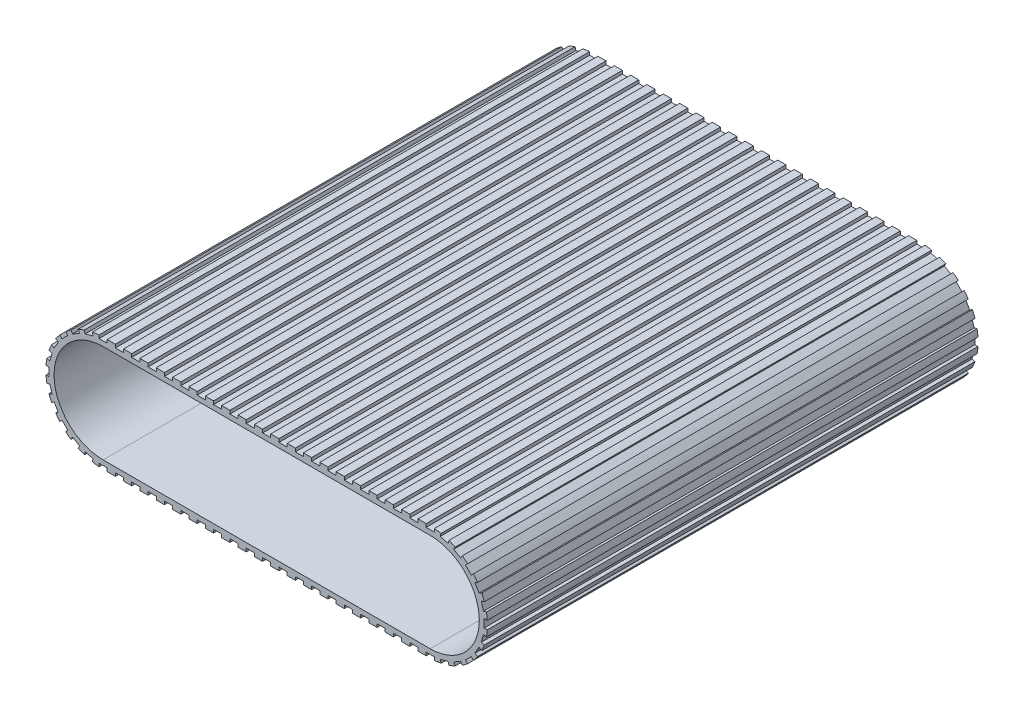
SolidWorks part; units mm, degrees
ref_plane "前视基准面" through (0, 0, 0) normal (0, 0, 1) x (1, 0, 0)
ref_plane "上视基准面" through (0, 0, 0) normal (0, 1, 0) x (1, 0, 0)
ref_plane "右视基准面" through (0, 0, 0) normal (1, 0, 0) x (0, 0, -1)
sketch "草图1" plane through (0, 0, 0) normal (0, 0, 1) x (1, 0, 0)
  line L0 (-100, 0) -> (100, 0) construction
  line L1 (-100, 35) -> (100, 35)
  line L2 (-100, -35) -> (100, -35)
  line L3 (-100, 0) -> (100, 0) construction
  line L4 (-100, 30) -> (100, 30)
  line L5 (-100, -30) -> (100, -30)
  arc A0 (-100, 35) -> (-100, -35) centre (-100, 0) ccw
  arc A1 (100, -35) -> (100, 35) centre (100, 0) ccw
  arc A2 (-100, 30) -> (-100, -30) centre (-100, 0) ccw
  arc A3 (100, -30) -> (100, 30) centre (100, 0) ccw
  point P3 (0, 0)
  point P8 (0, 0)
  dimension "D1" = 35
  dimension "D3" = 30
  dimension "D2" = 200
extrude "凸台-拉伸1" add sketch "草图1" along normal mid plane 300
sketch "草图2" plane through (0, 35, 0) normal (0, 1, 0) x (1, 0, 0)
  line L0 (100, -150) -> (-100, -150) construction
  line L1 (2.5, 150) -> (-2.5, 150)
  line L2 (2.5, 150) -> (2.5, -150)
  line L3 (2.5, -150) -> (-2.5, -150)
  line L4 (-2.5, 150) -> (-2.5, -150)
  line L5 (0, -150) -> (0, 150) construction
  line L6 (2.5, 0) -> (-2.5, 0) construction
  line L7 (12.5, 150) -> (12.5, -150)
  line L8 (12.5, 150) -> (7.5, 150)
  line L9 (7.5, 150) -> (7.5, -150)
  line L10 (12.5, -150) -> (7.5, -150)
  line L11 (22.5, 150) -> (22.5, -150)
  line L12 (22.5, 150) -> (17.5, 150)
  line L13 (17.5, 150) -> (17.5, -150)
  line L14 (22.5, -150) -> (17.5, -150)
  line L15 (32.5, 150) -> (32.5, -150)
  line L16 (32.5, 150) -> (27.5, 150)
  line L17 (27.5, 150) -> (27.5, -150)
  line L18 (32.5, -150) -> (27.5, -150)
  line L19 (42.5, 150) -> (42.5, -150)
  line L20 (42.5, 150) -> (37.5, 150)
  line L21 (37.5, 150) -> (37.5, -150)
  line L22 (42.5, -150) -> (37.5, -150)
  line L23 (52.5, 150) -> (52.5, -150)
  line L24 (52.5, 150) -> (47.5, 150)
  line L25 (47.5, 150) -> (47.5, -150)
  line L26 (52.5, -150) -> (47.5, -150)
  line L27 (62.5, 150) -> (62.5, -150)
  line L28 (62.5, 150) -> (57.5, 150)
  line L29 (57.5, 150) -> (57.5, -150)
  line L30 (62.5, -150) -> (57.5, -150)
  line L31 (72.5, 150) -> (72.5, -150)
  line L32 (72.5, 150) -> (67.5, 150)
  line L33 (67.5, 150) -> (67.5, -150)
  line L34 (72.5, -150) -> (67.5, -150)
  line L35 (82.5, 150) -> (82.5, -150)
  line L36 (82.5, 150) -> (77.5, 150)
  line L37 (77.5, 150) -> (77.5, -150)
  line L38 (82.5, -150) -> (77.5, -150)
  line L39 (92.5, 150) -> (92.5, -150)
  line L40 (92.5, 150) -> (87.5, 150)
  line L41 (87.5, 150) -> (87.5, -150)
  line L42 (92.5, -150) -> (87.5, -150)
  line L43 (102.5, 150) -> (102.5, -150)
  line L44 (102.5, 150) -> (97.5, 150)
  line L45 (97.5, 150) -> (97.5, -150)
  line L46 (102.5, -150) -> (97.5, -150)
  line L47 (-102.5, -150) -> (-97.5, -150)
  line L48 (-92.5, -150) -> (-87.5, -150)
  line L49 (-82.5, -150) -> (-77.5, -150)
  line L50 (-72.5, -150) -> (-67.5, -150)
  line L51 (-62.5, -150) -> (-57.5, -150)
  line L52 (-52.5, -150) -> (-47.5, -150)
  line L53 (-42.5, -150) -> (-37.5, -150)
  line L54 (-32.5, -150) -> (-27.5, -150)
  line L55 (-22.5, -150) -> (-17.5, -150)
  line L56 (-12.5, -150) -> (-7.5, -150)
  line L57 (-97.5, 150) -> (-97.5, -150)
  line L58 (-102.5, 150) -> (-97.5, 150)
  line L59 (-102.5, 150) -> (-102.5, -150)
  line L60 (-87.5, 150) -> (-87.5, -150)
  line L61 (-92.5, 150) -> (-87.5, 150)
  line L62 (-92.5, 150) -> (-92.5, -150)
  line L63 (-77.5, 150) -> (-77.5, -150)
  line L64 (-82.5, 150) -> (-77.5, 150)
  line L65 (-82.5, 150) -> (-82.5, -150)
  line L66 (-67.5, 150) -> (-67.5, -150)
  line L67 (-72.5, 150) -> (-67.5, 150)
  line L68 (-72.5, 150) -> (-72.5, -150)
  line L69 (-57.5, 150) -> (-57.5, -150)
  line L70 (-62.5, 150) -> (-57.5, 150)
  line L71 (-62.5, 150) -> (-62.5, -150)
  line L72 (-47.5, 150) -> (-47.5, -150)
  line L73 (-52.5, 150) -> (-47.5, 150)
  line L74 (-52.5, 150) -> (-52.5, -150)
  line L75 (-37.5, 150) -> (-37.5, -150)
  line L76 (-42.5, 150) -> (-37.5, 150)
  line L77 (-42.5, 150) -> (-42.5, -150)
  line L78 (-27.5, 150) -> (-27.5, -150)
  line L79 (-32.5, 150) -> (-27.5, 150)
  line L80 (-32.5, 150) -> (-32.5, -150)
  line L81 (-17.5, 150) -> (-17.5, -150)
  line L82 (-22.5, 150) -> (-17.5, 150)
  line L83 (-22.5, 150) -> (-22.5, -150)
  line L84 (-7.5, 150) -> (-7.5, -150)
  line L85 (-12.5, 150) -> (-7.5, 150)
  line L86 (-12.5, 150) -> (-12.5, -150)
  point P0 (0, 0)
  dimension "D1" = 5
  dimension "D2" = 11
extrude "切除-拉伸1" cut sketch "草图2" against normal blind 2
mirror "镜向1" about plane through (0, 0, 0) normal (0, 1, 0) of "切除-拉伸1"
ref_plane "基准面1" through (135, 0, 0) normal (1, 0, 0) x (0, 0, -1)
sketch "草图3" plane through (135, 0, 0) normal (1, 0, 0) x (0, 0, -1)
  line L0 (150, -34.9106) -> (150, 34.9106) construction
  line L1 (-150, 2.5) -> (150, 2.5)
  line L2 (-150, 2.5) -> (-150, -2.5)
  line L3 (-150, -2.5) -> (150, -2.5)
  line L4 (150, 2.5) -> (150, -2.5)
  line L5 (0, -2.5) -> (0, 2.5) construction
  line L6 (-150, 0) -> (150, 0) construction
  point P0 (0, 0)
  dimension "D1" = 5
extrude "切除-拉伸2" cut sketch "草图3" against normal blind 2
pattern_circular "阵列(圆周)1" count 6 every 15 about axis through (100, 0, 0) along (0, 0, 1) of "切除-拉伸2"
mirror "镜向2" about plane through (0, 0, 0) normal (0, 1, 0) of "阵列(圆周)1"
mirror "镜向3" about plane through (0, 0, 0) normal (1, 0, 0) of "镜向2", "阵列(圆周)1"
